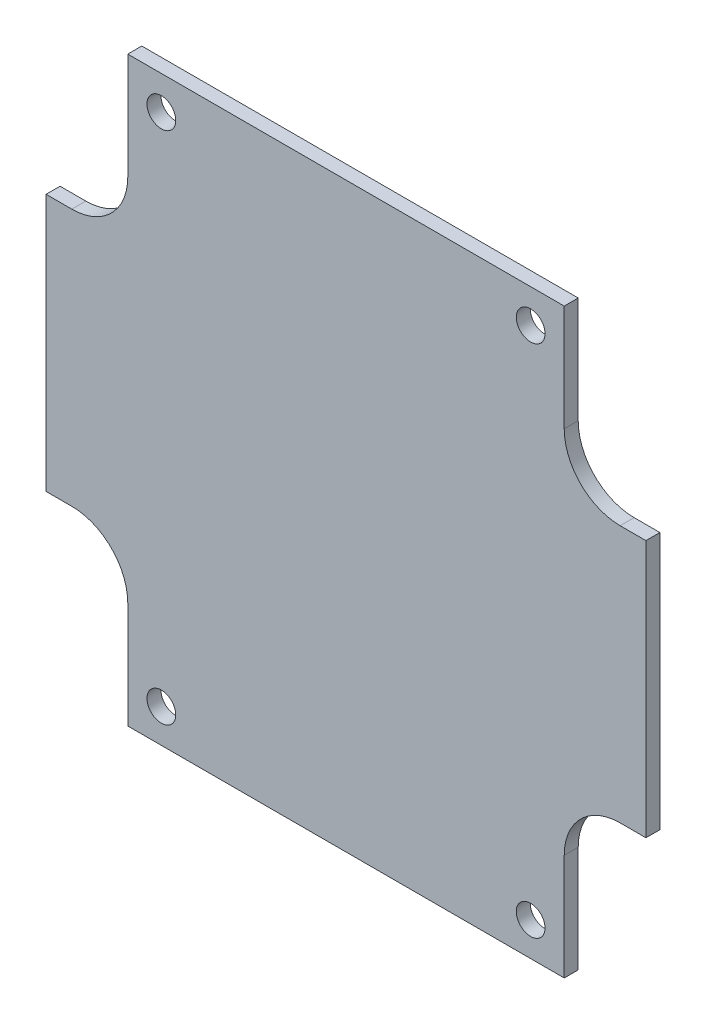
SolidWorks part; units mm, degrees
ref_plane "Front Plane" through (0, 0, 0) normal (0, 0, 1) x (1, 0, 0)
ref_plane "Top Plane" through (0, 0, 0) normal (0, 1, 0) x (1, 0, 0)
ref_plane "Right Plane" through (0, 0, 0) normal (1, 0, 0) x (0, 0, -1)
sketch "Sketch1" plane through (0, 0, 0) normal (0, 0, 1) x (1, 0, 0)
  line L0 (0, 47.625) -> (0, 18.415)
  line L1 (0, 18.415) -> (2.921, 18.415)
  line L2 (9.271, 12.065) -> (9.271, 0)
  line L3 (9.271, 0) -> (58.801, 0)
  line L4 (0, 33.02) -> (34.036, 33.02) construction
  line L5 (34.036, 33.02) -> (34.036, 0) construction
  line L6 (58.801, 12.065) -> (58.801, 0)
  line L7 (68.072, 18.415) -> (65.151, 18.415)
  line L8 (68.072, 47.625) -> (68.072, 18.415)
  line L9 (9.271, 53.975) -> (9.271, 66.04)
  line L10 (0, 47.625) -> (2.921, 47.625)
  line L11 (9.271, 66.04) -> (58.801, 66.04)
  line L12 (68.072, 47.625) -> (65.151, 47.625)
  line L13 (58.801, 53.975) -> (58.801, 66.04)
  arc A0 (2.921, 18.415) -> (9.271, 12.065) centre (2.921, 12.065) cw
  arc A1 (65.151, 18.415) -> (58.801, 12.065) centre (65.151, 12.065) ccw
  arc A2 (58.801, 53.975) -> (65.151, 47.625) centre (65.151, 53.975) ccw
  arc A3 (9.271, 53.975) -> (2.921, 47.625) centre (2.921, 53.975) cw
  point P21 (68.072, 33.02)
  point P23 (58.801, 47.625)
  dimension "D5" = 6.35
  dimension "D1" = 24.765
  dimension "D2" = 34.036
  dimension "D3" = 33.02
  dimension "D4" = 14.605
extrude "Boss-Extrude1" add sketch "Sketch1" along normal blind 1.5875
sketch "Sketch3" plane through (0, 0, 1.5875) normal (0, 0, 1) x (1, 0, 0)
  line L113 (0, 33.02) -> (68.072, 33.02) construction
  line L114 (68.072, 33.02) -> (34.036, 33.02) construction
  line L115 (34.036, 33.02) -> (34.036, 66.04) construction
  line L125 (65.151, 18.415) -> (68.072, 18.415)
  line L126 (58.801, 0) -> (58.801, 12.065)
  line L127 (9.271, 0) -> (58.801, 0)
  line L128 (9.271, 12.065) -> (9.271, 0)
  line L129 (0, 18.415) -> (2.921, 18.415)
  line L130 (0, 47.625) -> (0, 18.415)
  line L131 (2.921, 47.625) -> (0, 47.625)
  line L132 (9.271, 66.04) -> (9.271, 53.975)
  line L133 (58.801, 66.04) -> (9.271, 66.04)
  line L134 (68.072, 47.625) -> (65.151, 47.625)
  line L135 (58.801, 53.975) -> (58.801, 66.04)
  line L136 (68.072, 18.415) -> (68.072, 47.625)
  line L137 (65.151, 18.415) -> (68.072, 18.415)
  line L138 (58.801, 0) -> (58.801, 12.065)
  line L139 (9.271, 0) -> (58.801, 0)
  line L140 (9.271, 12.065) -> (9.271, 0)
  line L141 (0, 18.415) -> (2.921, 18.415)
  line L142 (0, 47.625) -> (0, 18.415)
  line L143 (2.921, 47.625) -> (0, 47.625)
  line L144 (9.271, 66.04) -> (9.271, 53.975)
  line L145 (58.801, 66.04) -> (9.271, 66.04)
  line L146 (68.072, 47.625) -> (65.151, 47.625)
  line L147 (58.801, 53.975) -> (58.801, 66.04)
  line L148 (68.072, 18.415) -> (68.072, 47.625)
  circle A36 centre (13.081, 62.23) radius 1.6319
  circle A37 centre (54.991, 62.23) radius 1.632
  circle A38 centre (54.991, 3.81) radius 1.632
  circle A39 centre (13.081, 3.81) radius 1.6319
  arc A40 (65.151, 18.415) -> (58.801, 12.065) centre (65.151, 12.065) ccw
  arc A41 (9.271, 12.065) -> (2.921, 18.415) centre (2.921, 12.065) ccw
  arc A42 (2.921, 47.625) -> (9.271, 53.975) centre (2.921, 53.975) ccw
  arc A43 (58.801, 53.975) -> (65.151, 47.625) centre (65.151, 53.975) ccw
  arc A44 (65.151, 18.415) -> (58.801, 12.065) centre (65.151, 12.065) ccw
  arc A45 (9.271, 12.065) -> (2.921, 18.415) centre (2.921, 12.065) ccw
  arc A46 (2.921, 47.625) -> (9.271, 53.975) centre (2.921, 53.975) ccw
  arc A47 (58.801, 53.975) -> (65.151, 47.625) centre (65.151, 53.975) ccw
  dimension "D2" = 3.2639
  dimension "D3" = 3.81
  dimension "D4" = 3.81
  dimension "D1" = 0
extrude "Cut-Extrude1" cut sketch "Sketch3" against normal through all contours A37 | A38 | A39 | A36
